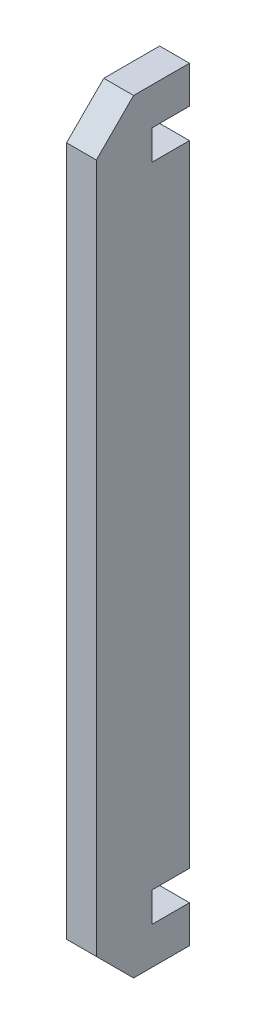
SolidWorks part; units mm, degrees
ref_plane "Front Plane" through (0, 0, 0) normal (1, 0, 0) x (0, 1, 0)
ref_plane "Top Plane" through (0, 0, 0) normal (0, 0, 1) x (0, 1, 0)
ref_plane "Right Plane" through (0, 0, 0) normal (0, 1, 0) x (-1, 0, 0)
sketch "Sketch1" plane through (0, 0, 0) normal (1, 0, 0) x (0, 1, 0)
  line L0 (-17.9216, 5.2239) -> (66.6784, 5.2239)
  line L1 (-26.9216, 0.2239) -> (75.6784, 0.2239)
  line L2 (-26.9216, 0.2239) -> (-26.9216, 12.7239)
  line L3 (-26.9216, 12.7239) -> (75.6784, 12.7239)
  line L4 (75.6784, 0.2239) -> (75.6784, 12.7239)
  line L5 (-21.9216, 0.2239) -> (-17.9216, 0.2239)
  line L6 (-21.9216, 0.2239) -> (-21.9216, 5.2239)
  line L7 (-21.9216, 5.2239) -> (-17.9216, 5.2239)
  line L8 (-17.9216, 0.2239) -> (-17.9216, 5.2239)
  line L9 (66.6784, 0.2239) -> (70.6784, 0.2239)
  line L10 (66.6784, 0.2239) -> (66.6784, 5.2239)
  line L11 (66.6784, 5.2239) -> (70.6784, 5.2239)
  line L12 (70.6784, 0.2239) -> (70.6784, 5.2239)
  line L13 (24.3784, 5.2239) -> (24.3784, 0.2239)
  dimension "D1" = 12.5
  dimension "D2" = 4
  dimension "D3" = 4
  dimension "D4" = 84.6
  dimension "D5" = 5
  dimension "D6" = 5
  dimension "D7" = 102.6
extrude "Boss-Extrude1" add sketch "Sketch1" along normal blind 4 contours L12 L1 L4 L3 L2 L6 L7 L0 L11 | L13 L0 L8 L1 | L0 L13 L1 L10
chamfer "Chamfer1" distance 5 angle 45 2 edges at (2, 75.6784, 12.7239) (2, -26.9216, 12.7239)
